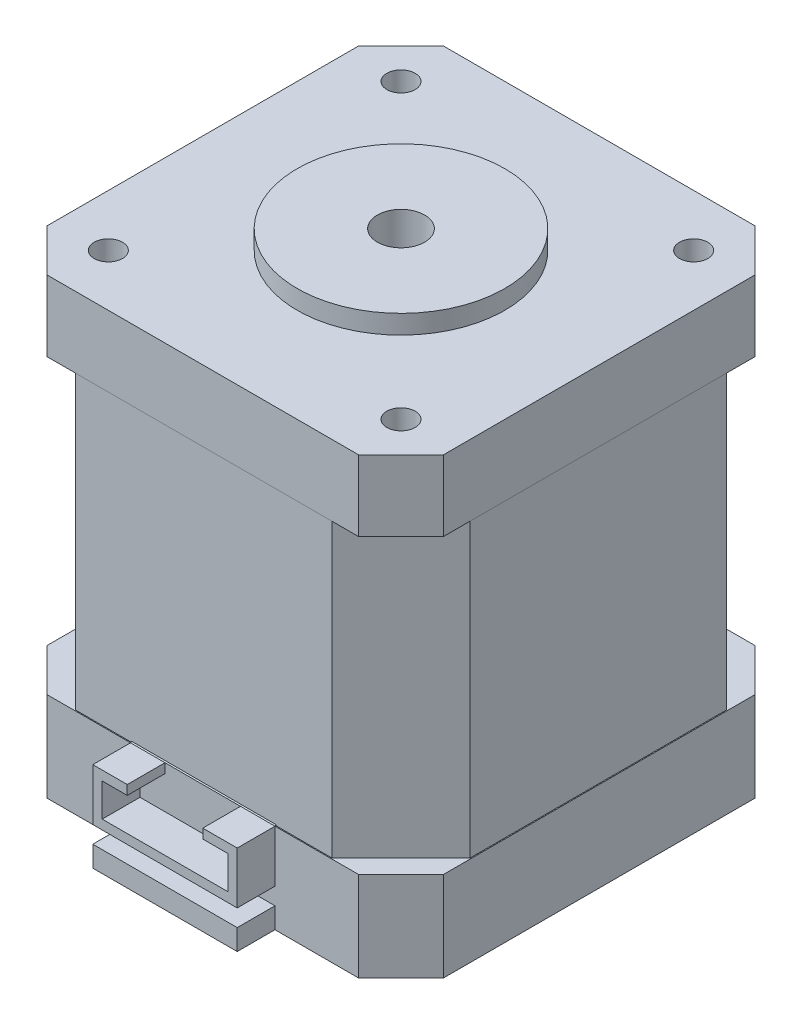
SolidWorks part; units mm, degrees
ref_plane "前视基准面" through (0, 0, 0) normal (0, 0, 1) x (1, 0, 0)
ref_plane "上视基准面" through (0, 0, 0) normal (0, 1, 0) x (1, 0, 0)
ref_plane "右视基准面" through (0, 0, 0) normal (1, 0, 0) x (0, 0, -1)
other "Configuration Table"
sketch "草图1" plane through (0, 0, 0) normal (0, 1, 0) x (1, 0, 0)
  line L1 (-21, -21) -> (21, -21)
  line L2 (-21, -21) -> (-21, 21)
  line L3 (-21, 21) -> (21, 21)
  line L4 (21, -21) -> (21, 21)
  line L5 (-21, -21) -> (21, 21) construction
  line L6 (-21, 21) -> (21, -21) construction
  point P0 (0, 0)
  dimension "D1" = 42
  dimension "D2" = 42
extrude "凸台-拉伸1" add sketch "草图1" along normal blind 48
sketch "草图2" plane through (0, 0, 0) normal (0, 1, 0) x (1, 0, 0)
  line L0 (-21, 21) -> (-16.5, 21)
  line L1 (21, 21) -> (-21, 21) construction
  line L2 (-16.5, 21) -> (-21, 16.5)
  line L3 (-21, 21) -> (-21, -21) construction
  line L4 (-21, 16.5) -> (-21, 21)
  line L5 (-1000, 0) -> (49000, 0) construction
  line L6 (0, -1000) -> (0, 49000) construction
  line L7 (21, 16.5) -> (21, 21)
  line L8 (16.5, 21) -> (21, 16.5)
  line L9 (21, 21) -> (16.5, 21)
  line L10 (21, -21) -> (16.5, -21)
  line L11 (16.5, -21) -> (21, -16.5)
  line L12 (21, -16.5) -> (21, -21)
  line L13 (-21, -16.5) -> (-21, -21)
  line L14 (-16.5, -21) -> (-21, -16.5)
  line L15 (-21, -21) -> (-16.5, -21)
  dimension "D1" = 4.5
  dimension "D2" = 4.5
extrude "切除-拉伸1" cut sketch "草图2" against normal up to surface (48 mm away) from surface at 48 up to face at (0, 0, 0) starting at face at (0, 48, 0)
sketch "草图3" plane through (0, 0, 0) normal (0, 1, 0) x (1, 0, 0)
  line L0 (-1000, 0) -> (49000, 0) construction
  line L1 (0, -1000) -> (0, 49000) construction
  line L2 (-21, 13.5) -> (-21, 21)
  line L3 (-21, 16.5) -> (-21, -16.5) construction
  line L4 (-21, 21) -> (-13.5, 21)
  line L5 (16.5, 21) -> (-16.5, 21) construction
  line L6 (-13.5, 21) -> (-21, 13.5)
  line L7 (13.5, 21) -> (21, 13.5)
  line L8 (21, 21) -> (13.5, 21)
  line L9 (21, 13.5) -> (21, 21)
  line L10 (21, -13.5) -> (21, -21)
  line L11 (21, -21) -> (13.5, -21)
  line L12 (13.5, -21) -> (21, -13.5)
  line L13 (-13.5, -21) -> (-21, -13.5)
  line L14 (-21, -21) -> (-13.5, -21)
  line L15 (-21, -13.5) -> (-21, -21)
  dimension "D1" = 7.5
  dimension "D2" = 7.5
extrude "切除-拉伸2" cut sketch "草图3" along normal blind 31 from offset 9.5
sketch "草图4" plane through (0, 0, 0) normal (0, 0, 1) x (1, 0, 0)
  line L1 (-16.5, 40.5) -> (16.5, 40.5)
  line L2 (-16.5, 40.5) -> (-16.5, 9.5)
  line L3 (-16.5, 9.5) -> (16.5, 9.5)
  line L4 (16.5, 40.5) -> (16.5, 9.5)
extrude "切除-拉伸3" cut sketch "草图4" along normal blind 0.1 from surface at -21 starting at face at (0, 24.6667, -21)
sketch "草图5" plane through (0, 0, 0) normal (0, 0, 1) x (1, 0, 0)
  line L1 (-16.5, 40.5) -> (16.5, 40.5)
  line L2 (-16.5, 40.5) -> (-16.5, 9.5)
  line L3 (-16.5, 9.5) -> (16.5, 9.5)
  line L4 (16.5, 40.5) -> (16.5, 9.5)
extrude "切除-拉伸4" cut sketch "草图5" against normal blind 0.1 from surface at 21 starting at face at (0, 24.6667, 21)
sketch "草图6" plane through (0, 0, 0) normal (1, 0, 0) x (0, 0, -1)
  line L1 (-16.5, 40.5) -> (16.5, 40.5)
  line L2 (-16.5, 40.5) -> (-16.5, 9.5)
  line L3 (-16.5, 9.5) -> (16.5, 9.5)
  line L4 (16.5, 40.5) -> (16.5, 9.5)
extrude "切除-拉伸5" cut sketch "草图6" along normal blind 0.1 from surface at -21 starting at face at (-21, 24.6667, 0)
sketch "草图7" plane through (0, 0, 0) normal (1, 0, 0) x (0, 0, -1)
  line L1 (-16.5, 40.5) -> (16.5, 40.5)
  line L2 (-16.5, 40.5) -> (-16.5, 9.5)
  line L3 (-16.5, 9.5) -> (16.5, 9.5)
  line L4 (16.5, 40.5) -> (16.5, 9.5)
extrude "切除-拉伸6" cut sketch "草图7" against normal blind 0.1 from surface at 21 starting at face at (21, 24.6667, 0)
sketch "草图8" plane through (0, 0, 0) normal (0, 1, 0) x (1, 0, 0)
  line L1 (-15.5, -15.5) -> (15.5, -15.5) construction
  line L2 (-15.5, -15.5) -> (-15.5, 15.5) construction
  line L3 (-15.5, 15.5) -> (15.5, 15.5) construction
  line L4 (15.5, -15.5) -> (15.5, 15.5) construction
  line L5 (-15.5, -15.5) -> (15.5, 15.5) construction
  line L6 (-15.5, 15.5) -> (15.5, -15.5) construction
  circle A0 centre (-15.5, 15.5) radius 1.5
  circle A1 centre (15.5, 15.5) radius 1.5
  circle A2 centre (-15.5, -15.5) radius 1.5
  circle A3 centre (15.5, -15.5) radius 1.5
  point P0 (0, 0)
  dimension "D3" = 3
  dimension "D4" = 3
  dimension "D5" = 3
  dimension "D6" = 3
  dimension "D1" = 31
  dimension "D2" = 31
sketch "草图17" plane through (0, 0, 0) normal (0, 1, 0) x (1, 0, 0)
  circle A0 centre (0, 0) radius 4.75
  dimension "D1" = 9.5
extrude "切除-拉伸9" cut sketch "草图17" along normal blind 3
sketch "草图18" plane through (0, 0, 0) normal (0, 1, 0) x (1, 0, 0)
  circle A0 centre (0, 0) radius 11
  dimension "D1" = 22
extrude "凸台-拉伸2" add sketch "草图18" along normal blind 2 from surface at 48 starting at face at (0, 48, 0)
sketch "草图20" plane through (0, 0, 0) normal (0, 1, 0) x (1, 0, 0)
  circle A0 centre (0, 0) radius 2.5
  dimension "D1" = 5
extrude "切除-拉伸10" cut sketch "草图20" against normal up to surface (47 mm away) from surface at 50 up to face at (0, 3, 4.75) starting at face at (0, 50, -11)
sketch "草图21" plane through (0, 0, 0) normal (0, 0, 1) x (1, 0, 0)
  line L0 (-16.5, 0) -> (16.5, 0) construction
  line L1 (-7.65, 2.2) -> (7.65, 2.2)
  line L2 (-7.65, 2.2) -> (-7.65, 0)
  line L3 (-7.65, 0) -> (7.65, 0)
  line L4 (7.65, 2.2) -> (7.65, 0)
  point P6 (0, 2.2)
  dimension "D1" = 15.3
  dimension "D2" = 2.2
extrude "凸台-拉伸3" add sketch "草图21" along normal blind 4 from surface at 21 starting at face at (0, 4.75, 21)
sketch "草图22" plane through (0, 0, 0) normal (0, 0, 1) x (1, 0, 0)
  line L0 (-13.6, 9.5) -> (13.6, 9.5) construction
  line L1 (-7.65, 9.5) -> (7.65, 9.5)
  line L2 (-7.65, 9.5) -> (-7.65, 4)
  line L3 (-7.65, 4) -> (7.65, 4)
  line L4 (7.65, 9.5) -> (7.65, 4)
  line L7 (7.65, 0) -> (7.65, 2.2) construction
  line L8 (-7.65, 2.2) -> (-7.65, 0) construction
  dimension "D1" = 5.5
extrude "凸台-拉伸4" add sketch "草图22" along normal blind 4 from surface at 21 starting at face at (0, 2.925, 21)
sketch "草图23" plane through (0, 0, 0) normal (0, 0, 1) x (1, 0, 0)
  line L0 (-4, 8.5) -> (4, 8.5) construction
  line L1 (-7.65, 9.5) -> (7.65, 9.5) construction
  line L2 (-7.65, 9.5) -> (-7.65, 4) construction
  line L3 (-7.65, 4) -> (7.65, 4) construction
  line L4 (7.65, 9.5) -> (7.65, 4) construction
  line L5 (-6.65, 8.5) -> (6.65, 8.5) construction
  line L6 (-6.65, 8.5) -> (-6.65, 5)
  line L7 (-6.65, 5) -> (6.65, 5)
  line L8 (6.65, 8.5) -> (6.65, 5)
  line L9 (-4, 8.5) -> (-4, 9.5)
  line L10 (-4, 9.5) -> (4, 9.5)
  line L11 (4, 9.5) -> (4, 8.5)
  line L12 (-6.65, 8.5) -> (-4, 8.5)
  line L13 (6.65, 8.5) -> (4, 8.5)
  point P13 (0, 8.5)
  dimension "D1" = 13.3
  dimension "D2" = 1
  dimension "D3" = 3.5
  dimension "D4" = 1
  dimension "D5" = 8
extrude "切除-拉伸11" cut sketch "草图23" against normal up to surface (21 mm away) from surface
sketch "草图26" plane through (0, 0, 0) normal (1, 0, 0) x (0, 0, -1)
  line L0 (-21, 9.5) -> (-20.9, 9.5)
  line L1 (-20.9, 9.5) -> (-20.9, 9.6013)
  line L2 (-20.9, 9.6013) -> (-21, 9.5)
  dimension "D1" = 0.1013
extrude "凸台-拉伸5" add sketch "草图26" against normal up to surface (7.65 mm away) from surface
extrude "切除-拉伸12" cut sketch "草图8" against normal through all from surface at 48 starting at face at (0, 48, -11)
